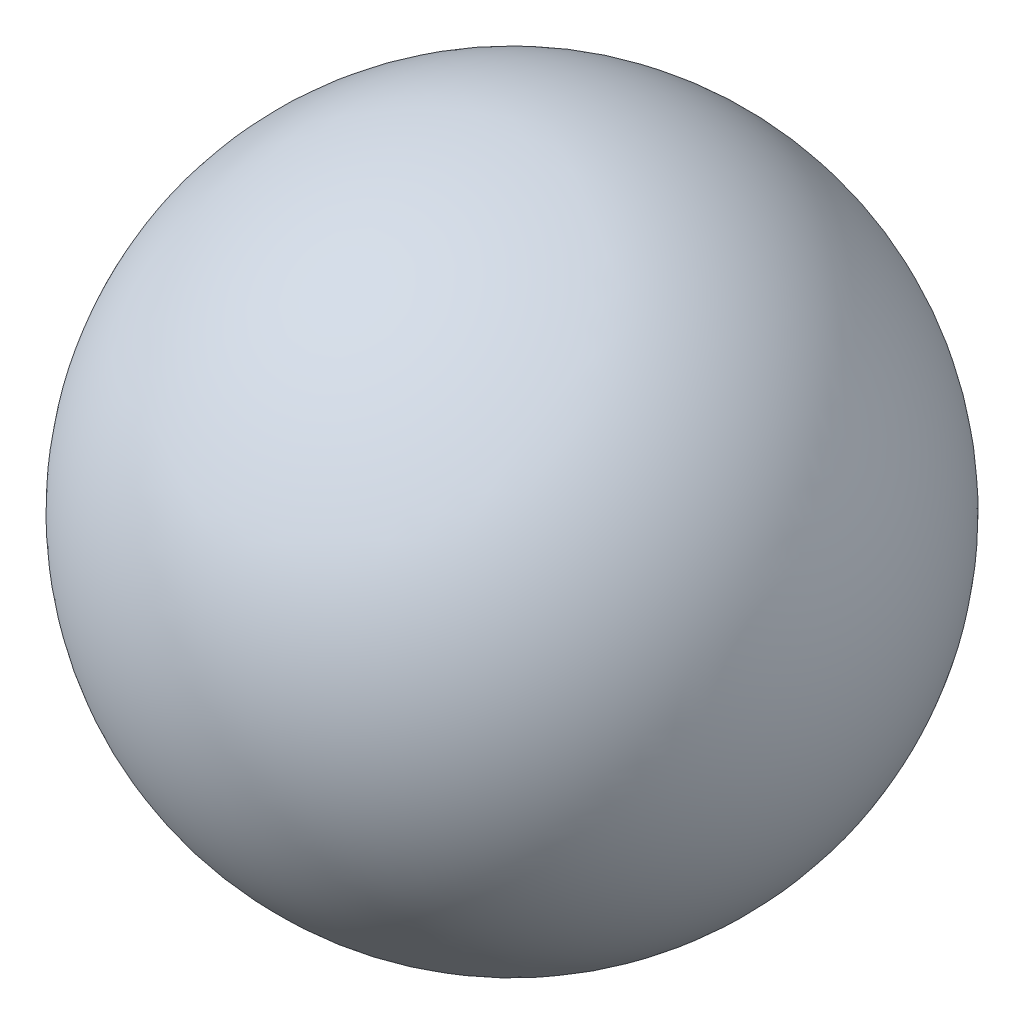
SolidWorks part; units mm, degrees
material "Rubber"
ref_plane "Front Plane" through (0, 0, 0) normal (0, 0, 1) x (1, 0, 0)
ref_plane "Top Plane" through (0, 0, 0) normal (0, 1, 0) x (1, 0, 0)
ref_plane "Right Plane" through (0, 0, 0) normal (1, 0, 0) x (0, 0, -1)
sketch "Sketch2" plane through (0, 0, 0) normal (0, 1, 0) x (1, 0, 0)
  line L0 (-34.925, 0) -> (34.925, 0)
  arc A0 (34.925, 0) -> (-34.925, 0) centre (0, 0) cw
revolve "Revolve1" add sketch "Sketch2" angle 360 about L0
